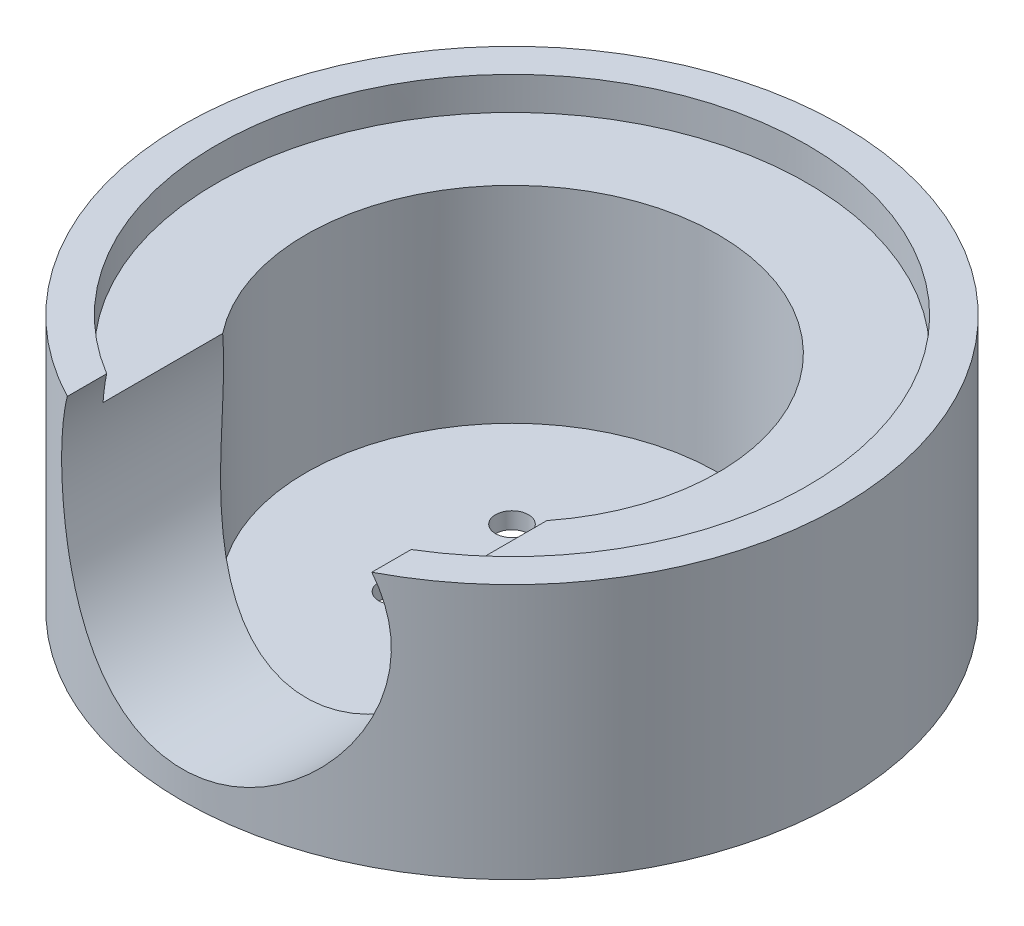
SolidWorks part; units mm, degrees
ref_plane "Front Plane" through (0, 0, 0) normal (0, 0, 1) x (1, 0, 0)
ref_plane "Top Plane" through (0, 0, 0) normal (0, 1, 0) x (1, 0, 0)
ref_plane "Right Plane" through (0, 0, 0) normal (1, 0, 0) x (0, 0, -1)
sketch "Sketch1" plane through (0, 0, 0) normal (0, 1, 0) x (1, 0, 0)
  line L0 (4.2426, 4.2426) -> (4.2426, -4.2426) construction
  line L1 (4.2426, -4.2426) -> (-4.2426, -4.2426) construction
  line L2 (-4.2426, -4.2426) -> (-4.2426, 4.2426) construction
  line L3 (-4.2426, 4.2426) -> (4.2426, 4.2426) construction
  circle A0 centre (0, 0) radius 24
  circle A1 centre (4.2426, 4.2426) radius 1.2
  circle A2 centre (-4.2426, 4.2426) radius 1.2
  circle A3 centre (4.2426, -4.2426) radius 1.2
  circle A4 centre (-4.2426, -4.2426) radius 1.2
  circle A5 centre (0, 0) radius 6 construction
  dimension "D1" = 48
  dimension "D2" = 2.4
  dimension "D3" = 2.4
  dimension "D4" = 2.4
  dimension "D5" = 2.4
  dimension "D6" = 12
extrude "Boss-Extrude1" add sketch "Sketch1" along normal blind 1.2
sketch "Sketch2" plane through (0, 1.2, 0) normal (0, 1, 0) x (1, 0, 0)
  circle A0 centre (0, 0) radius 15
  circle A1 centre (0, 0) radius 24 construction
  circle A2 centre (0, 0) radius 24
  dimension "D1" = 30
extrude "Boss-Extrude2" add sketch "Sketch2" along normal blind 15
sketch "Sketch3" plane through (0, 16.2, 0) normal (0, 1, 0) x (1, 0, 0)
  circle A0 centre (0, 0) radius 24 construction
  circle A1 centre (0, 0) radius 24
  circle A2 centre (0, 0) radius 21.5
  dimension "D1" = 43
extrude "Boss-Extrude3" add sketch "Sketch3" along normal blind 2.4
sketch "Sketch4" plane through (0, 16.2, 0) normal (0, 1, 0) x (1, 0, 0)
  line L0 (-12, -30) -> (12, -30)
  line L1 (0, 0) -> (0, -30) construction
  line L2 (-12, -30) -> (-12, 0)
  line L3 (-12, 0) -> (12, 0)
  line L4 (12, 0) -> (12, -30)
  dimension "D1" = 24
  dimension "D2" = 30
ref_plane "Plane1" through (0, 0, 24) normal (0, 0, 1) x (1, 0, 0)
sketch "Sketch5" plane through (0, 0, 24) normal (0, 0, 1) x (1, 0, 0)
  line L0 (-24, 0) -> (24, 0) construction
  line L1 (24, 18.6) -> (-24, 18.6) construction
  line L2 (-24, 0) -> (24, 0) construction
  line L3 (24, 18.6) -> (-24, 18.6) construction
  line L4 (0, 14) -> (0, 18.6) construction
  circle A0 centre (0, 14) radius 12
  dimension "D1" = 24
  dimension "D2" = 14
extrude "Cut-Extrude2" cut sketch "Sketch5" against normal blind 20
sketch "Sketch6" plane through (0, 0, 0) normal (0, -1, 0) x (1, 0, 0)
  circle A0 centre (0, 0) radius 19
  circle A1 centre (0, 0) radius 20
  dimension "D1" = 40
  dimension "D2" = 38
extrude "Cut-Extrude3" cut sketch "Sketch6" against normal blind 1.6
